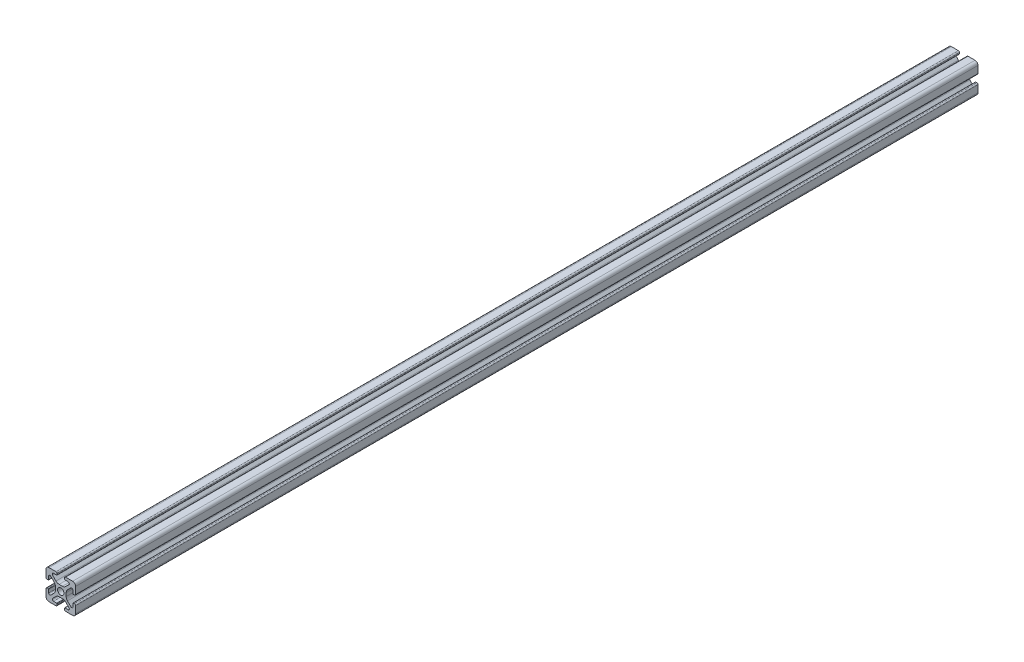
SolidWorks part; units mm, degrees
ref_plane "Front Plane" through (0, 0, 0) normal (0, 0, 1) x (1, 0, 0)
ref_plane "Top Plane" through (0, 0, 0) normal (0, 1, 0) x (1, 0, 0)
ref_plane "Right Plane" through (0, 0, 0) normal (1, 0, 0) x (0, 0, -1)
sketch "Sketch1" plane through (0, 0, 0) normal (0, 0, 1) x (1, 0, 0)
  line L2 (-9.9949, 7.9883) -> (-9.9949, 3.2893)
  line L3 (-7.9883, 9.9949) -> (-3.2893, 9.9949)
  line L4 (-2.5019, 9.2075) -> (-2.5019, 8.4963)
  line L5 (-2.8067, 8.1915) -> (-4.9149, 8.1915)
  line L6 (-5.5076, 6.7606) -> (-3.2528, 4.5058)
  line L7 (-6.7606, 5.5076) -> (-4.5058, 3.2528)
  line L8 (-8.1915, 4.9149) -> (-8.1915, 2.8067)
  line L9 (-8.4963, 2.5019) -> (-9.2075, 2.5019)
  line L11 (-1.1334, 3.6279) -> (1.1334, 3.6279)
  line L12 (-3.6279, 1.1334) -> (-3.6279, -1.1334)
  line L13 (8.4963, 2.5019) -> (9.2075, 2.5019)
  line L14 (8.1915, 4.9149) -> (8.1915, 2.8067)
  line L15 (9.9949, 7.9883) -> (9.9949, 3.2893)
  line L16 (7.9883, 9.9949) -> (3.2893, 9.9949)
  line L17 (2.5019, 9.2075) -> (2.5019, 8.4963)
  line L18 (2.8067, 8.1915) -> (4.9149, 8.1915)
  line L19 (3.6279, 1.1334) -> (3.6279, -1.1334)
  line L20 (5.5076, 6.7606) -> (3.2528, 4.5058)
  line L21 (6.7606, 5.5076) -> (4.5058, 3.2528)
  line L22 (-8.4963, -2.5019) -> (-9.2075, -2.5019)
  line L23 (-8.1915, -4.9149) -> (-8.1915, -2.8067)
  line L24 (-6.7606, -5.5076) -> (-4.5058, -3.2528)
  line L25 (-5.5076, -6.7606) -> (-3.2528, -4.5058)
  line L26 (-2.8067, -8.1915) -> (-4.9149, -8.1915)
  line L27 (-2.5019, -9.2075) -> (-2.5019, -8.4963)
  line L28 (-7.9883, -9.9949) -> (-3.2893, -9.9949)
  line L29 (-9.9949, -7.9883) -> (-9.9949, -3.2893)
  line L30 (9.9949, -7.9883) -> (9.9949, -3.2893)
  line L31 (7.9883, -9.9949) -> (3.2893, -9.9949)
  line L32 (2.5019, -9.2075) -> (2.5019, -8.4963)
  line L33 (2.8067, -8.1915) -> (4.9149, -8.1915)
  line L34 (5.5076, -6.7606) -> (3.2528, -4.5058)
  line L35 (6.7606, -5.5076) -> (4.5058, -3.2528)
  line L36 (8.1915, -4.9149) -> (8.1915, -2.8067)
  line L37 (8.4963, -2.5019) -> (9.2075, -2.5019)
  line L38 (-1.1334, -3.6279) -> (1.1334, -3.6279)
  circle A0 centre (0, 0) radius 2.1463
  arc A1 (-9.9949, 7.9883) -> (-7.9883, 9.9949) centre (-7.9883, 7.9883) cw
  arc A2 (-6.7606, 5.5076) -> (-8.1915, 4.9149) centre (-7.3533, 4.9149) ccw
  arc A3 (-4.9149, 8.1915) -> (-5.5076, 6.7606) centre (-4.9149, 7.3533) ccw
  arc A4 (-3.2893, 9.9949) -> (-2.5019, 9.2075) centre (-3.2893, 9.2075) cw
  arc A5 (-9.9949, 3.2893) -> (-9.2075, 2.5019) centre (-9.2075, 3.2893) ccw
  arc A6 (-8.1915, 2.8067) -> (-8.4963, 2.5019) centre (-8.4963, 2.8067) cw
  arc A7 (-2.5019, 8.4963) -> (-2.8067, 8.1915) centre (-2.8067, 8.4963) cw
  arc A8 (-1.1334, 3.6279) -> (-3.2528, 4.5058) centre (-1.1334, 6.6251) cw
  arc A9 (-3.6279, 1.1334) -> (-4.5058, 3.2528) centre (-6.6251, 1.1334) ccw
  arc A10 (8.1915, 2.8067) -> (8.4963, 2.5019) centre (8.4963, 2.8067) ccw
  arc A11 (9.9949, 3.2893) -> (9.2075, 2.5019) centre (9.2075, 3.2893) cw
  arc A12 (9.9949, 7.9883) -> (7.9883, 9.9949) centre (7.9883, 7.9883) ccw
  arc A13 (3.2893, 9.9949) -> (2.5019, 9.2075) centre (3.2893, 9.2075) ccw
  arc A14 (2.5019, 8.4963) -> (2.8067, 8.1915) centre (2.8067, 8.4963) ccw
  arc A15 (1.1334, 3.6279) -> (3.2528, 4.5058) centre (1.1334, 6.6251) ccw
  arc A16 (3.6279, 1.1334) -> (4.5058, 3.2528) centre (6.6251, 1.1334) cw
  arc A17 (6.7606, 5.5076) -> (8.1915, 4.9149) centre (7.3533, 4.9149) cw
  arc A18 (4.9149, 8.1915) -> (5.5076, 6.7606) centre (4.9149, 7.3533) cw
  arc A19 (-3.6279, -1.1334) -> (-4.5058, -3.2528) centre (-6.6251, -1.1334) cw
  arc A20 (-1.1334, -3.6279) -> (-3.2528, -4.5058) centre (-1.1334, -6.6251) ccw
  arc A21 (-2.5019, -8.4963) -> (-2.8067, -8.1915) centre (-2.8067, -8.4963) ccw
  arc A22 (-8.1915, -2.8067) -> (-8.4963, -2.5019) centre (-8.4963, -2.8067) ccw
  arc A23 (-9.9949, -3.2893) -> (-9.2075, -2.5019) centre (-9.2075, -3.2893) cw
  arc A24 (-3.2893, -9.9949) -> (-2.5019, -9.2075) centre (-3.2893, -9.2075) ccw
  arc A25 (-4.9149, -8.1915) -> (-5.5076, -6.7606) centre (-4.9149, -7.3533) cw
  arc A26 (-6.7606, -5.5076) -> (-8.1915, -4.9149) centre (-7.3533, -4.9149) cw
  arc A27 (-9.9949, -7.9883) -> (-7.9883, -9.9949) centre (-7.9883, -7.9883) ccw
  arc A28 (9.9949, -7.9883) -> (7.9883, -9.9949) centre (7.9883, -7.9883) cw
  arc A29 (6.7606, -5.5076) -> (8.1915, -4.9149) centre (7.3533, -4.9149) ccw
  arc A30 (4.9149, -8.1915) -> (5.5076, -6.7606) centre (4.9149, -7.3533) ccw
  arc A31 (3.2893, -9.9949) -> (2.5019, -9.2075) centre (3.2893, -9.2075) cw
  arc A32 (9.9949, -3.2893) -> (9.2075, -2.5019) centre (9.2075, -3.2893) ccw
  arc A33 (8.1915, -2.8067) -> (8.4963, -2.5019) centre (8.4963, -2.8067) cw
  arc A34 (2.5019, -8.4963) -> (2.8067, -8.1915) centre (2.8067, -8.4963) cw
  arc A35 (1.1334, -3.6279) -> (3.2528, -4.5058) centre (1.1334, -6.6251) cw
  arc A36 (3.6279, -1.1334) -> (4.5058, -3.2528) centre (6.6251, -1.1334) ccw
extrude "Boss-Extrude1" add sketch "Sketch1" along normal mid plane 609.6
